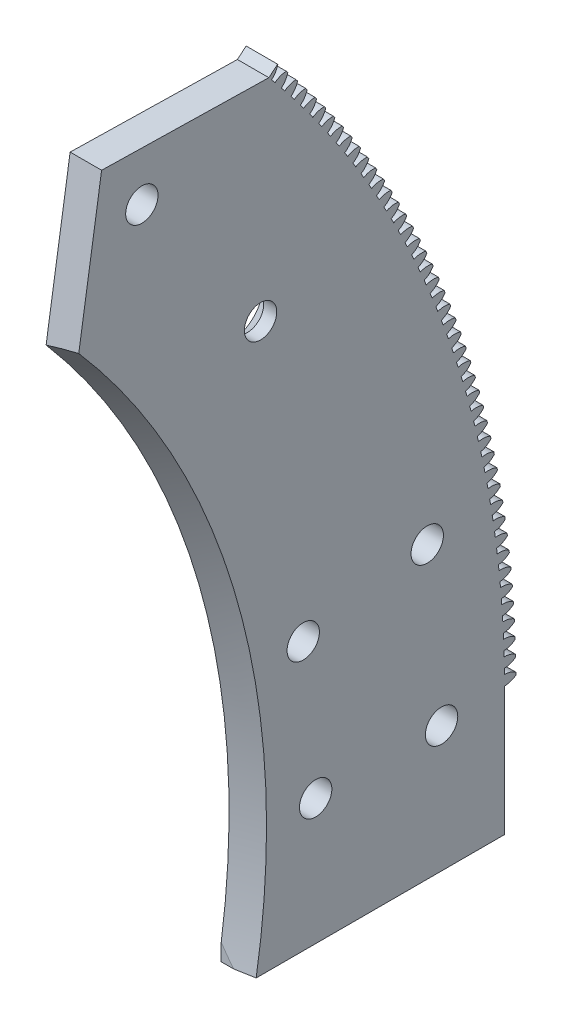
SolidWorks part; units mm, degrees
material "ABS"
ref_plane "Front Plane" through (0, 0, 0) normal (0, 0, 1) x (1, 0, 0)
ref_plane "Top Plane" through (0, 0, 0) normal (0, 1, 0) x (1, 0, 0)
ref_plane "Right Plane" through (0, 0, 0) normal (1, 0, 0) x (0, 0, -1)
ref_plane "Plane2" through (6.35, 0, 0) normal (1, 0, 0) x (0, 0, -1)
sketch "Sketch1" plane through (0, 0, 0) normal (1, 0, 0) x (0, 0, -1)
  line L0 (-1000, 0) -> (152.4, 0) construction
  line L1 (152.4, 0) -> (152.4, -25.4)
  line L2 (0, 0) -> (116.7452, 97.9608) construction
  line L4 (203.2, 0) -> (49000, 0) construction
  line L7 (152.4, -25.4) -> (203.2, -25.4)
  line L8 (203.2, 0) -> (203.2, -25.4)
  line L10 (-19.9245, -15.6845) -> (159.6649, 125.6875) construction
  line L61 (160.8976, 124.1056) -> (0, 0) construction
  line L62 (136.2027, 114.2876) -> (121.9167, 131.313) construction
  line L63 (116.7452, 97.9608) -> (121.9167, 131.313)
  line L67 (121.9167, 131.313) -> (155.6602, 130.6144)
  line L68 (0, 0) -> (35966.99, 34732.9185) construction
  line L69 (159.6736, 125.6943) -> (159.6985, 125.714) construction
  arc A2 (152.4, 0) -> (116.7452, 97.9608) centre (0, 0) ccw
  circle A19 centre (0, 0) radius 203.2 construction
  arc A22 (155.6602, 130.6144) -> (203.2, 0) centre (0, 0) cw
  point P6 (159.6985, 125.714)
  point P7 (116.7452, 97.9608)
  dimension "D1" = 152.4
  dimension "D2" = 6.35
  dimension "D12" = 406.4
  dimension "D3" = 40
  dimension "D4" = 50.8
  dimension "D5" = 25.4
  dimension "D11" = 22.225
  dimension "D13" = 44
sketch "Sketch2" plane through (6.35, 0, 0) normal (1, 0, 0) x (0, 0, -1)
  line L0 (0, 0) -> (165.1, 0) construction
  line L1 (165.1, 0) -> (190.5, 0) construction
  line L2 (0, 0) -> (49240.3877, 8682.4089) construction
  circle A0 centre (165.1, 0) radius 3.2639
  circle A1 centre (190.5, 0) radius 3.2639
  arc A3 (165.1, 0) -> (162.5918, 28.6693) centre (0, 0) ccw construction
  circle A4 centre (162.5918, 28.6693) radius 3.2639
  arc A5 (190.5, 0) -> (187.6059, 33.08) centre (0, 0) ccw construction
  circle A6 centre (187.6059, 33.08) radius 3.2639
  dimension "D3" = 6.5278
  dimension "D4" = 6.5278
  dimension "D6" = 6.5278
  dimension "D7" = 6.5278
  dimension "D1" = 165.1
  dimension "D2" = 25.4
  dimension "D5" = 10
sketch "Sketch3" plane through (6.35, 0, 0) normal (1, 0, 0) x (0, 0, -1)
  line L0 (0, 0) -> (114.3, 0) construction
  line L1 (0, 0) -> (153.9793, 88.9) construction
  circle A0 centre (153.9793, 88.9) radius 3.2639
  dimension "D4" = 6.5278
  dimension "D1" = 114.3
  dimension "D2" = 30
  dimension "D3" = 177.8
sketch "Sketch11" plane through (6.35, 0, 0) normal (1, 0, 0) x (0, 0, -1)
  line L0 (-785.502, -659.1144) -> (0, 0) construction
  line L2 (-1000, 0) -> (0, 0) construction
  line L3 (203.2, 0) -> (205.5, 0)
  line L4 (155.6602, 130.6144) -> (157.4221, 132.0929)
  line L5 (157.4221, 132.0929) -> (921.7047, 773.4021) construction
  line L6 (-1000, 0) -> (49000, 0) construction
  arc A0 (-230, 0) -> (-176.1902, -147.8412) centre (0, 0) ccw construction
  arc A1 (-205.5, 0) -> (-157.4221, -132.0929) centre (0, 0) ccw construction
  arc A2 (-203.1, 0) -> (-155.5836, -130.5502) centre (0, 0) ccw construction
  arc A3 (205.5, 0) -> (157.4221, 132.0929) centre (0, 0) ccw
  arc A4 (230, 0) -> (176.1902, 147.8412) centre (0, 0) ccw construction
  arc A5 (-203.1, 0) -> (-155.5836, -130.5502) centre (0, 0) ccw
  arc A6 (155.6602, 130.6144) -> (203.2, 0) centre (0, 0) cw
  dimension "D1" = 460
  dimension "D2" = 411
  dimension "D3" = 2.4
  dimension "D4" = 40
  dimension "D5" = 2.3
extrude "Boss-Extrude2" add sketch "Sketch11" against normal blind 6.35
extrude "Boss-Extrude3" add sketch "Sketch1" along normal blind 6.35
sketch "Sketch12" plane through (6.35, 0, 0) normal (1, 0, 0) x (0, 0, -1)
  line L0 (0, 0) -> (205.5, 0) construction
  line L1 (203.2, 0) -> (205.5, 0) construction
  line L2 (204.4985, 0.7854) -> (204.4985, -0.7854) construction
  line L3 (0, 0) -> (203.1992, 0.5545) construction
  line L4 (202.3406, 0) -> (206.4945, 1.5119) construction
  line L5 (0, 0) -> (206.4939, 1.5861) construction
  line L6 (204.4985, 0.7854) -> (204.4864, 2.3561) construction
  circle A0 centre (0, 0) radius 204.5 construction
  arc A1 (205.5, 0) -> (157.4221, 132.0929) centre (0, 0) ccw construction
  circle A2 centre (0, 0) radius 203.2 construction
  arc A3 (203.1992, 0.5545) -> (206.4856, 2.4358) centre (203.1888, 4.3838) ccw
  arc A4 (206.5, 0) -> (206.4856, -2.4358) centre (0, 0) cw
  arc A5 (203.1992, -0.5545) -> (206.4856, -2.4358) centre (203.1888, -4.3838) cw
  arc A6 (206.5, 0) -> (158.1882, 132.7356) centre (0, 0) ccw
  arc A7 (206.5, 0) -> (206.4856, 2.4358) centre (0, 0) ccw
  arc A8 (203.1992, 0.5545) -> (203.1992, -0.5545) centre (0, 0) cw
  dimension "D1" = 409
  dimension "D5" = 406.4
  dimension "D3" = 20
  dimension "D4" = 0.44
  dimension "D2" = 1
extrude "Cut-Extrude4" cut sketch "Sketch12" against normal blind 6.35
pattern_circular "CirPattern3" count 100 every 0.88 about axis through (0, 0, 0) along (1, 0, 0) of "Cut-Extrude4"
extrude "Cut-Extrude5" cut sketch "Sketch2" against normal blind 6.35
extrude "Cut-Extrude6" cut sketch "Sketch3" against normal blind 6.35
sketch "Sketch15" plane through (6.35, 0, 0) normal (1, 0, 0) x (0, 0, -1)
  line L0 (0, 0) -> (130.0347, 121.2593) construction
  line L1 (-196961.5506, -34729.6355) -> (246201.9383, 43412.0444) construction
  circle A0 centre (130.0347, 121.2593) radius 3.2639
  dimension "D3" = 6.5278
  dimension "D1" = 177.8
  dimension "D2" = 33
extrude "Cut-Extrude7" cut sketch "Sketch15" against normal through all
sketch "Sketch17" plane through (0, 0, 0) normal (-1, 0, 0) x (0, 0, 1)
  line L0 (0, 0) -> (-10825.3175, 6250) construction
  line L1 (0, 0) -> (-10825.3175, 6250) construction
sketch "Sketch18" plane through (6.35, 0, 0) normal (1, 0, 0) x (0, 0, -1)
  line L0 (0, 0) -> (10825.3175, 6250) construction
ref_plane "Plane1" through (0, 0, 0) normal (0, 0.866, 0.5) x (1, 0, 0)
sketch "Sketch19" plane through (0, 0, 0) normal (0, 0.866, 0.5) x (1, 0, 0)
  line L0 (0, 0) -> (0, 324.1975) construction
  line L1 (0, 177.8) -> (0, 170.815)
  line L2 (0, 177.8) -> (6.985, 177.8)
  line L3 (6.985, 177.8) -> (0, 170.815)
  point P3 (0, 177.8)
  dimension "D1" = 177.8
  dimension "D2" = 6.985
  dimension "D3" = 6.985
revolve "Cut-Revolve1" cut sketch "Sketch19" angle 360 about L2
sketch "Sketch21" plane through (0, 0, 0) normal (0, 1, 0) x (1, 0, 0)
  line L0 (0, 0) -> (25.4, 0) construction
  line L1 (25.4, 0) -> (25.4, 38.1) construction
  line L2 (0, 0) -> (-6.35, 0) construction
  line L3 (-6.35, 0) -> (-6.35, 152.4) construction
  line L4 (25.4, 38.1) -> (144.0278, 38.1)
  line L5 (25.4, 38.1) -> (-93.2278, 38.1)
  line L6 (-1006.35, 0) -> (48993.65, 0) construction
  arc A0 (144.0278, 38.1) -> (-93.2278, 38.1) centre (25.4, 38.1) ccw
  dimension "D1" = 25.4
  dimension "D2" = 38.1
  dimension "D3" = 6.35
  dimension "D4" = 152.4
revolve "Cut-Revolve2" cut sketch "Sketch21" angle 360 about L6
equation "\"Module\"= 1mm"
equation "\"Number of Teeth\"= 409"
equation "\"D1@Sketch12\"=\"Module\" * \"Number of Teeth\""
equation "\"D4@Sketch12\"=180 / \"Number of Teeth\""
equation "\"D2\"= 360 / \"Number of Teeth\""
equation "\"D2@Sketch11\"=( \"Number of Teeth\" + 2) * \"Module\""
equation "\"D2@CirPattern3\"= 360 / \"Number of Teeth\""
